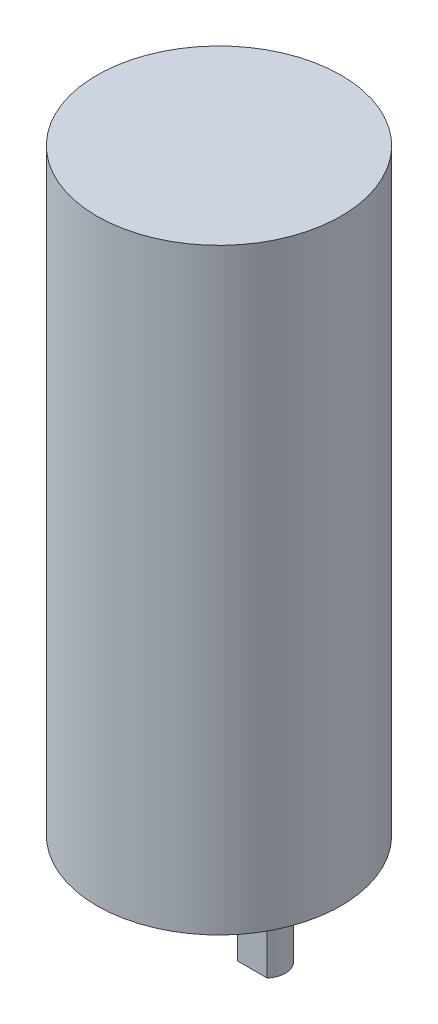
SolidWorks part; units mm, degrees
ref_plane "Alzado" through (0, 0, 0) normal (0, 0, 1) x (1, 0, 0)
ref_plane "Planta" through (0, 0, 0) normal (0, 1, 0) x (1, 0, 0)
ref_plane "Vista lateral" through (0, 0, 0) normal (1, 0, 0) x (0, 0, -1)
sketch "Croquis1" plane through (0, 0, 0) normal (0, 1, 0) x (1, 0, 0)
  circle A0 centre (0, 0) radius 18.4
  dimension "D1" = 36.8
extrude "Saliente-Extruir1" add sketch "Croquis1" along normal blind 90
sketch "Croquis2" plane through (0, 0, 0) normal (0, -1, 0) x (-1, 0, 0)
  circle A0 centre (0, 7) radius 3
  circle A1 centre (0, 0) radius 7 construction
  dimension "D1" = 6
  dimension "D2" = 14
extrude "Saliente-Extruir2" add sketch "Croquis2" along normal blind 20
hole_wizard "Taladro roscado M3x0.51" positions "Croquis4" profile "Croquis5" tap size "M3x0.5" standard "Ansi Metric"
sketch "Croquis4" plane through (0, 0, 0) normal (0, -1, 0) x (-1, 0, 0)
  line L0 (7.75, 13.4234) -> (-7.75, 13.4234) construction
  line L2 (0, 7) -> (0, 18.4) construction
  circle A0 centre (0, 0) radius 18.4 construction
  circle A2 centre (0, 0) radius 15.5 construction
  point P0 (-7.75, -13.4234)
  point P9 (-15.5, 0)
  point P10 (-7.75, 13.4234)
  point P11 (7.75, 13.4234)
  point P21 (15.5, 0)
  point P22 (7.75, -13.4234)
  dimension "D1" = 31
  dimension "D2" = 6
sketch "Croquis5" plane through (7.75, 0, 13.4234) normal (1, 0, 0) x (0, 0, -1)
  line L0 (0, 0) -> (0, 9.2511)
  line L1 (0, 9.2511) -> (1.25, 8.5)
  line L2 (1.25, 8.5) -> (1.25, 6)
  line L3 (1.25, 6) -> (1.5, 6)
  line L4 (1.5, 6) -> (1.5, 0)
  line L5 (1.5, 0) -> (0, 0)
  line L10 (0, 9.2511) -> (-1.25, 8.5) construction
  line L11 (0, -6.35) -> (0, 107.95) construction
  dimension "Diámetro de perforador para roscar" = 2.5
  dimension "Profundidad de perforador para roscar" = 8.5
  dimension "Diámetro mayor de rosca" = 3
  dimension "Profundidad de rosca" = 6
  dimension "Ángulo de perforador" = 118
sketch "Croquis7" plane through (0, 0, 0) normal (0, -1, 0) x (-1, 0, 0)
  circle A0 centre (0, 7) radius 6
  dimension "D1" = 12
extrude "Saliente-Extruir3" add sketch "Croquis7" along normal blind 6.5
sketch "Croquis8" plane through (0, 0, 0) normal (0, -1, 0) x (-1, 0, 0)
  arc A0 (-8.4811, 9.8524) -> (8.4811, 9.8524) centre (0, 0) ccw
  arc A1 (-8.4811, 9.8524) -> (8.4811, 9.8524) centre (0, 7) ccw
extrude "Cortar-Extruir1" cut sketch "Croquis8" against normal blind 2
sketch "Croquis9" plane through (0, -20, 0) normal (0, -1, 0) x (1, 0, 0)
  line L1 (-2.2361, -5) -> (2.2361, -5)
  line L2 (-2.2361, -5) -> (-2.2361, 5.2317)
  line L3 (-2.2361, 5.2317) -> (2.2361, 5.2317)
  line L4 (2.2361, -5) -> (2.2361, 5.2317)
  circle A1 centre (0, -7) radius 3 construction
  circle A2 centre (0, -7) radius 3 construction
  dimension "D1" = 2
extrude "Cortar-Extruir2" cut sketch "Croquis9" against normal blind 10
